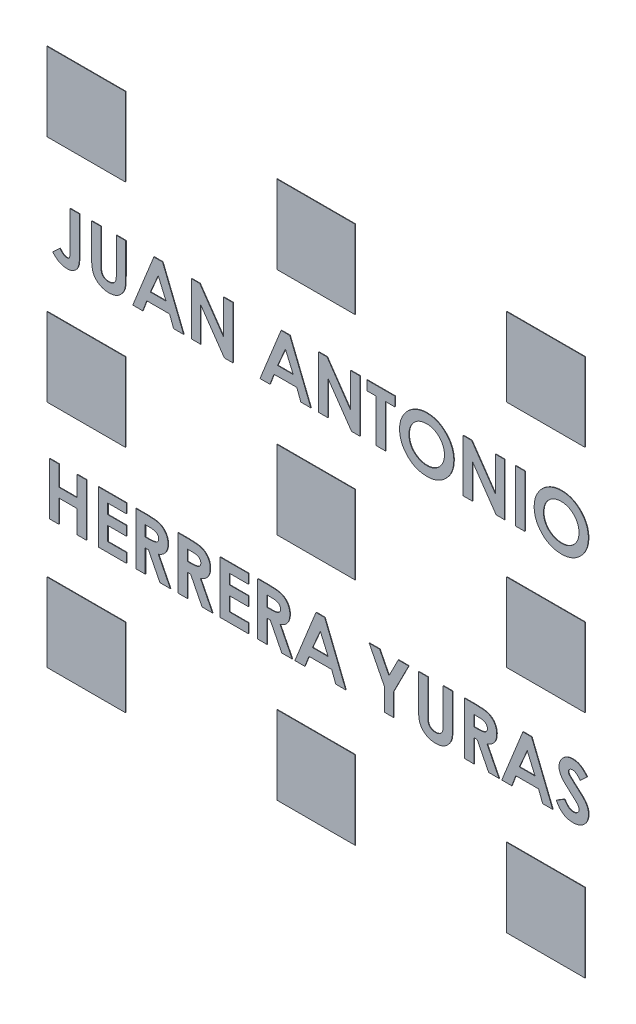
SolidWorks part; units mm, degrees
ref_plane "Front Plane" through (0, 0, 0) normal (0, 0, 1) x (1, 0, 0)
ref_plane "Top Plane" through (0, 0, 0) normal (0, 1, 0) x (1, 0, 0)
ref_plane "Right Plane" through (0, 0, 0) normal (1, 0, 0) x (0, 0, -1)
sketch "Sketch1" plane through (0, 0, 0) normal (0, 0, 1) x (1, 0, 0)
  line L0 (-88, -88) -> (88, -88) construction
  line L1 (110, -110) -> (-110, -110) construction
  line L2 (110, -110) -> (110, 110) construction
  line L3 (110, 110) -> (-110, 110) construction
  line L4 (-110, -110) -> (-110, 110) construction
  line L5 (110, -110) -> (-110, 110) construction
  line L6 (110, 110) -> (-110, -110) construction
  line L7 (-103, -103) -> (-73, -103)
  line L8 (-103, -103) -> (-103, -73)
  line L9 (-103, -73) -> (-73, -73)
  line L10 (-73, -103) -> (-73, -73)
  line L11 (-103, -103) -> (-73, -73) construction
  line L12 (-103, -73) -> (-73, -103) construction
  line L13 (88, -88) -> (88, 88) construction
  line L14 (88, 88) -> (-88, 88) construction
  line L15 (-88, 88) -> (-88, -88) construction
  line L16 (-15, -73) -> (15, -73)
  line L17 (-15, -103) -> (-15, -73)
  line L18 (-15, -103) -> (15, -103)
  line L19 (15, -103) -> (15, -73)
  line L20 (73, -73) -> (103, -73)
  line L21 (73, -103) -> (73, -73)
  line L22 (73, -103) -> (103, -103)
  line L23 (103, -103) -> (103, -73)
  line L24 (-15, 15) -> (15, 15)
  line L25 (-15, -15) -> (-15, 15)
  line L26 (-15, -15) -> (15, -15)
  line L27 (15, -15) -> (15, 15)
  line L28 (73, 15) -> (103, 15)
  line L29 (73, -15) -> (73, 15)
  line L30 (73, -15) -> (103, -15)
  line L31 (103, -15) -> (103, 15)
  line L32 (-15, 103) -> (15, 103)
  line L33 (-15, 73) -> (-15, 103)
  line L34 (-15, 73) -> (15, 73)
  line L35 (15, 73) -> (15, 103)
  line L36 (73, 103) -> (103, 103)
  line L37 (73, 73) -> (73, 103)
  line L38 (73, 73) -> (103, 73)
  line L39 (103, 73) -> (103, 103)
  line L40 (-103, 15) -> (-73, 15)
  line L41 (-103, -15) -> (-103, 15)
  line L42 (-103, -15) -> (-73, -15)
  line L43 (-73, -15) -> (-73, 15)
  line L44 (-103, 103) -> (-73, 103)
  line L45 (-103, 73) -> (-103, 103)
  line L46 (-103, 73) -> (-73, 73)
  line L47 (-73, 73) -> (-73, 103)
  text T0 "JUAN ANTONIO" font "Century Gothic" height 20
  text T1 "HERRERA YURAS" font "Century Gothic" height 20
  point P0 (0, 0)
  point P5 (-88, -88)
  dimension "D1" = 220
  dimension "D2" = 30
  dimension "D3" = 22
  dimension "D4" = 3
  dimension "D5" = 3
extrude "Boss-Extrude1" add sketch "Sketch1" along normal blind 0.2
